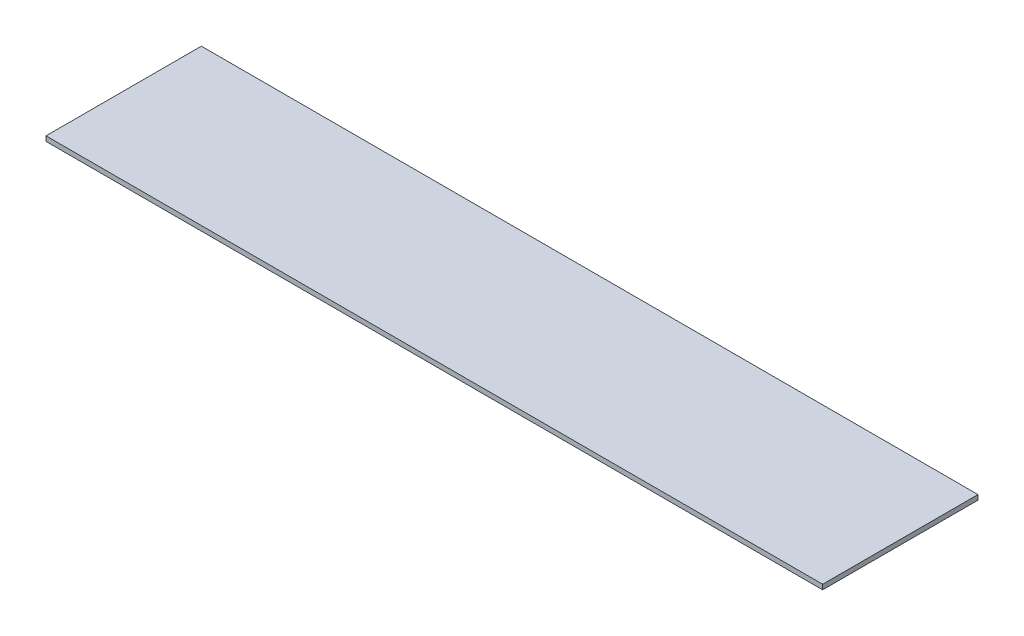
SolidWorks part; units mm, degrees
ref_plane "Front Plane" through (0, 0, 0) normal (0, 0, 1) x (1, 0, 0)
ref_plane "Top Plane" through (0, 0, 0) normal (0, 1, 0) x (1, 0, 0)
ref_plane "Right Plane" through (0, 0, 0) normal (1, 0, 0) x (0, 0, -1)
sketch "Sketch1" plane through (0, 0, 0) normal (0, 1, 0) x (1, 0, 0)
  line L1 (-254, -50.8) -> (254, -50.8)
  line L2 (-254, -50.8) -> (-254, 50.8)
  line L3 (-254, 50.8) -> (254, 50.8)
  line L4 (254, -50.8) -> (254, 50.8)
  line L5 (-254, -50.8) -> (254, 50.8) construction
  line L6 (-254, 50.8) -> (254, -50.8) construction
  point P0 (0, 0)
  dimension "D1" = 508
  dimension "D2" = 101.6
extrude "Boss-Extrude1" add sketch "Sketch1" along normal mid plane 3.175
